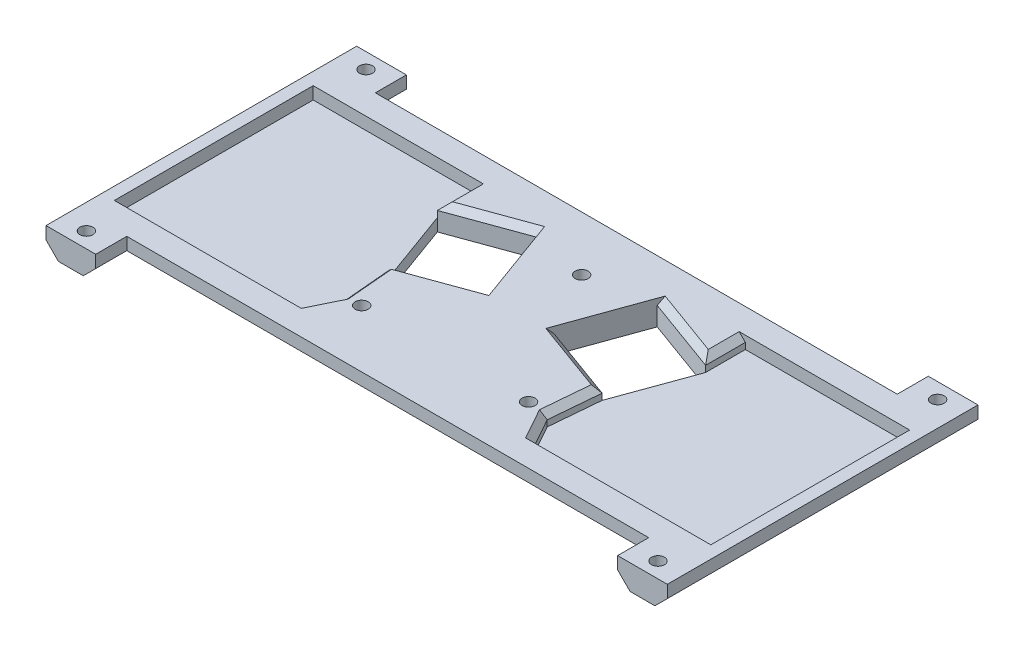
SolidWorks part; units mm, degrees
ref_plane "Спереди" through (0, 0, 0) normal (0, 0, 1) x (1, 0, 0)
ref_plane "Сверху" through (0, 0, 0) normal (0, 1, 0) x (1, 0, 0)
ref_plane "Справа" through (0, 0, 0) normal (1, 0, 0) x (0, 0, -1)
ref_plane "Плоскость4" through (0, 0, 0) normal (0, 1, 0) x (1, 0, 0)
sketch "Эскиз1" plane through (0, 0, 0) normal (0, 1, 0) x (1, 0, 0)
  line L0 (109.2898, 4.4193) -> (109.2898, 84.4193)
  line L1 (-90.7102, 4.4193) -> (109.2898, 4.4193)
  line L4 (-90.7102, 4.4193) -> (-90.7102, 84.4193)
  line L5 (-90.7102, 84.4193) -> (109.2898, 84.4193)
  line L6 (19.0891, 48.0793) -> (27.9153, 72.5359)
  line L9 (27.9153, 72.5359) -> (52.4117, 63.6199)
  line L10 (52.4117, 63.6199) -> (43.5326, 39.1938)
  line L11 (43.5326, 39.1938) -> (19.0891, 48.0793)
  line L12 (-33.9361, 63.6209) -> (-25.0432, 39.1877)
  line L13 (-25.0432, 39.1877) -> (-0.6112, 48.0803)
  line L14 (-0.6112, 48.0803) -> (-9.5041, 72.5134)
  line L15 (-9.5041, 72.5134) -> (-33.9361, 63.6209)
  circle A0 centre (9.2382, 66.8857) radius 2.1
  circle A1 centre (36.0962, 22.9414) radius 2.1
  circle A2 centre (-17.6197, 22.9414) radius 2.1
  point P18 (0, 0)
  point P20 (0, 0)
  point P31 (0, 0)
  point P32 (0, 0)
  point P33 (0, 0)
  point P34 (0, 0)
  point P35 (0, 0)
  point P36 (0, 0)
  point P37 (0, 0)
  point P38 (0, 0)
  point P39 (0, 0)
  point P40 (0, 0)
  point P41 (0, 0)
  point P42 (0, 0)
  point P43 (0, 0)
extrude "Бобышка-Вытянуть1" add sketch "Эскиз1" along normal blind 4
ref_plane "Плоскость5" through (0, 4, 0) normal (0, 1, 0) x (1, 0, 0)
sketch "Эскиз2" plane through (0, 4, 0) normal (0, 1, 0) x (1, 0, 0)
  line L0 (-90.7102, 84.4193) -> (-90.7102, 4.4193)
  line L2 (109.2898, 4.4193) -> (109.2898, 84.4193)
  line L3 (109.2898, 84.4193) -> (-90.7102, 84.4193) construction
  line L4 (109.2898, 4.4193) -> (109.2898, 84.4193) construction
  line L6 (-90.7102, 84.4193) -> (109.2898, 84.4193)
  line L7 (-90.7102, 4.4193) -> (109.2898, 4.4193)
  line L10 (-86.7102, 12.4193) -> (105.2898, 12.4193)
  line L11 (105.2898, 12.4193) -> (105.2898, 76.4193)
  line L12 (-86.7102, 12.4193) -> (-86.7102, 76.4193)
  line L13 (-86.7102, 76.4193) -> (105.2898, 76.4193)
  line L14 (-23.6197, 22.9414) -> (-25.0432, 39.1877)
  line L15 (-33.9361, 63.6209) -> (-9.5041, 72.5134)
  line L16 (-9.5041, 72.5134) -> (-0.6112, 48.0803)
  line L18 (30.0962, 22.9414) -> (-11.6197, 22.9414)
  line L19 (43.5326, 39.1938) -> (19.0891, 48.0793)
  line L20 (42.0962, 22.9414) -> (43.5326, 39.1938)
  line L22 (-25.0432, 39.1877) -> (-0.6112, 48.0803)
  line L23 (27.9153, 72.5359) -> (19.0891, 48.0793)
  line L24 (27.9153, 72.5359) -> (52.4117, 63.6199)
  line L25 (-23.6197, 22.9414) -> (-28.7779, 12.4193)
  line L26 (42.0962, 22.9414) -> (47.9722, 12.4193)
  line L27 (47.9722, 12.4193) -> (-28.7779, 12.4193)
  line L28 (-33.9361, 63.6209) -> (-33.9361, 76.4193)
  line L29 (52.4117, 63.6199) -> (52.4117, 76.4193)
  line L30 (52.4117, 76.4193) -> (-33.9361, 76.4193)
  circle A0 centre (9.2382, 66.8857) radius 2.1
  circle A1 centre (36.0962, 22.9414) radius 2.1
  circle A2 centre (-17.6197, 22.9414) radius 2.1
  circle A4 centre (-17.6197, 22.9414) radius 6
  circle A5 centre (36.0962, 22.9414) radius 6
extrude "Бобышка-Вытянуть4" add sketch "Эскиз2" along normal blind 4 contours A5 L20 L19 L23 L24 L29 L13 L28 L15 L16 L22 L14 A4 L18 A0 | A5 L18 A4 L25 L10 L26 | A5 A1 | A4 A2 | L0 L7 L2 L6 L12 L13 L11 L10
ref_plane "Плоскость6" through (0, 8, 0) normal (0, 1, 0) x (1, 0, 0)
sketch "Эскиз4" plane through (0, 8, 0) normal (0, 1, 0) x (1, 0, 0)
  line L0 (109.2898, 84.4193) -> (109.2898, 94.4193)
  line L2 (93.2898, 94.4193) -> (93.2898, 84.4193)
  line L3 (-90.7102, 84.4193) -> (109.2898, 84.4193) construction
  line L4 (93.2898, 84.4193) -> (109.2898, 84.4193)
  line L5 (-74.7102, 94.4193) -> (-74.7102, 84.4193)
  line L6 (109.2898, 4.4193) -> (109.2898, -5.5807)
  line L7 (109.2898, -5.5807) -> (93.2898, -5.5807)
  line L8 (-74.7102, 84.4193) -> (-90.7102, 84.4193)
  line L9 (93.2898, 94.4193) -> (109.2898, 94.4193)
  line L10 (-90.7102, 84.4193) -> (-90.7102, 94.4193)
  line L11 (-90.7102, 94.4193) -> (-74.7102, 94.4193)
  line L12 (109.2898, 4.4193) -> (93.2898, 4.4193)
  line L13 (-90.7102, 4.4193) -> (109.2898, 4.4193) construction
  line L14 (-90.7102, 4.4193) -> (-90.7102, -5.5807)
  line L15 (-90.7102, -5.5807) -> (-74.7102, -5.5807)
  line L16 (93.2898, 4.4193) -> (93.2898, -5.5807)
  line L17 (-74.7102, -5.5807) -> (-74.7102, 4.4193)
  line L18 (-74.7102, 4.4193) -> (-90.7102, 4.4193)
  circle A0 centre (-82.7102, 89.4193) radius 2.1
  circle A1 centre (101.2898, 89.4193) radius 2.1
  circle A2 centre (101.2898, -0.5807) radius 2.1
  circle A3 centre (-82.7102, -0.5807) radius 2.1
extrude "Бобышка-Вытянуть5" add sketch "Эскиз4" against normal blind 8
chamfer "Фаска2" distance 4 angle 45 8 edges at (109.2898, 0, -44.4193) (-90.7102, 0, -44.4193) (-74.7102, 0, 0.5807) (93.2898, 0, 0.5807) (9.2898, 0, -4.4193) (-74.7102, 0, -89.4193) (93.2898, 0, -89.4193) (9.2898, 0, -84.4193)
chamfer "Фаска3" distance 2 angle 45 10 edges at (-33.9361, 8, -70.0201) (-21.7201, 8, -68.0671) (-12.8272, 8, -43.634) (-24.3315, 8, -31.0646) (-26.1988, 8, -17.6804) (45.0342, 8, -17.6804) (42.8144, 8, -31.0676) (31.3109, 8, -43.6365) (40.1635, 8, -68.0779) (52.4117, 8, -70.0196)
